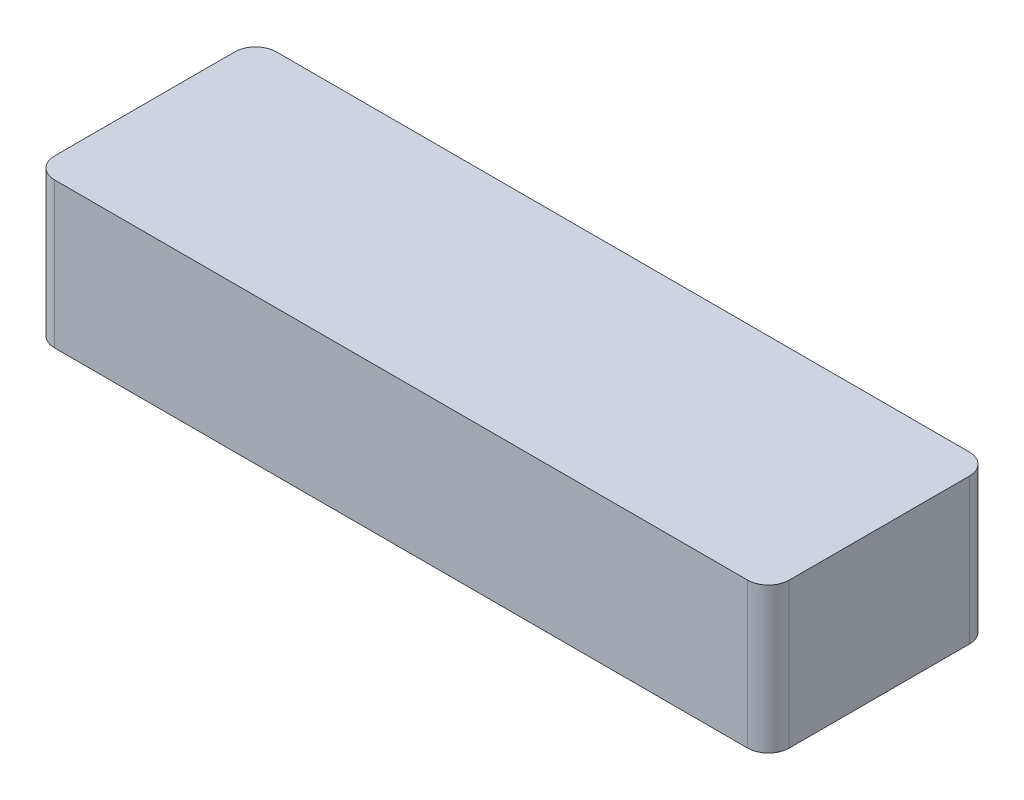
SolidWorks part; units mm, degrees
ref_plane "Front Plane" through (0, 0, 0) normal (0, 0, 1) x (1, 0, 0)
ref_plane "Top Plane" through (0, 0, 0) normal (0, 1, 0) x (1, 0, 0)
ref_plane "Right Plane" through (0, 0, 0) normal (1, 0, 0) x (0, 0, -1)
sketch "Sketch1" plane through (0, 0, 0) normal (0, 0, 1) x (1, 0, 0)
  line L1 (-84.0592, 9.1344) -> (21.9408, 9.1344)
  line L2 (-84.0592, 9.1344) -> (-84.0592, -11.8656)
  line L3 (-84.0592, -11.8656) -> (21.9408, -11.8656)
  line L4 (21.9408, 9.1344) -> (21.9408, -11.8656)
  dimension "D1" = 21
  dimension "1" = 106
extrude "Boss-Extrude1" add sketch "Sketch1" along normal blind 32
fillet "Fillet1" radius 3 4 edges at (-84.0592, -1.3656, 32) (-84.0592, -1.3656, 0) (21.9408, -1.3656, 0) (21.9408, -1.3656, 32)
